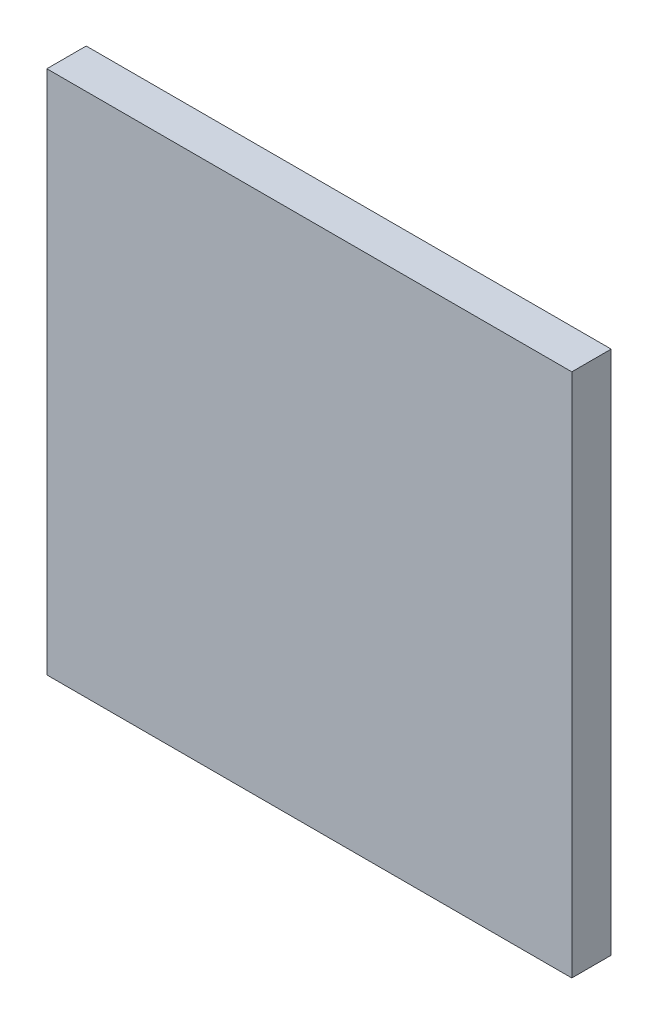
SolidWorks part; units mm, degrees
ref_plane "Front Plane" through (0, 0, 0) normal (0, 0, 1) x (1, 0, 0)
ref_plane "Top Plane" through (0, 0, 0) normal (0, 1, 0) x (1, 0, 0)
ref_plane "Right Plane" through (0, 0, 0) normal (1, 0, 0) x (0, 0, -1)
sketch "Sketch1" plane through (0, 0, 0) normal (0, 0, 1) x (1, 0, 0)
  line L1 (-100, -100) -> (100, -100)
  line L2 (-100, -100) -> (-100, 100)
  line L3 (-100, 100) -> (100, 100)
  line L4 (100, -100) -> (100, 100)
  line L5 (-100, -100) -> (100, 100) construction
  line L6 (-100, 100) -> (100, -100) construction
  point P0 (0, 0)
  dimension "D1" = 200
  dimension "D2" = 200
extrude "Boss-Extrude1" add sketch "Sketch1" along normal blind 15
